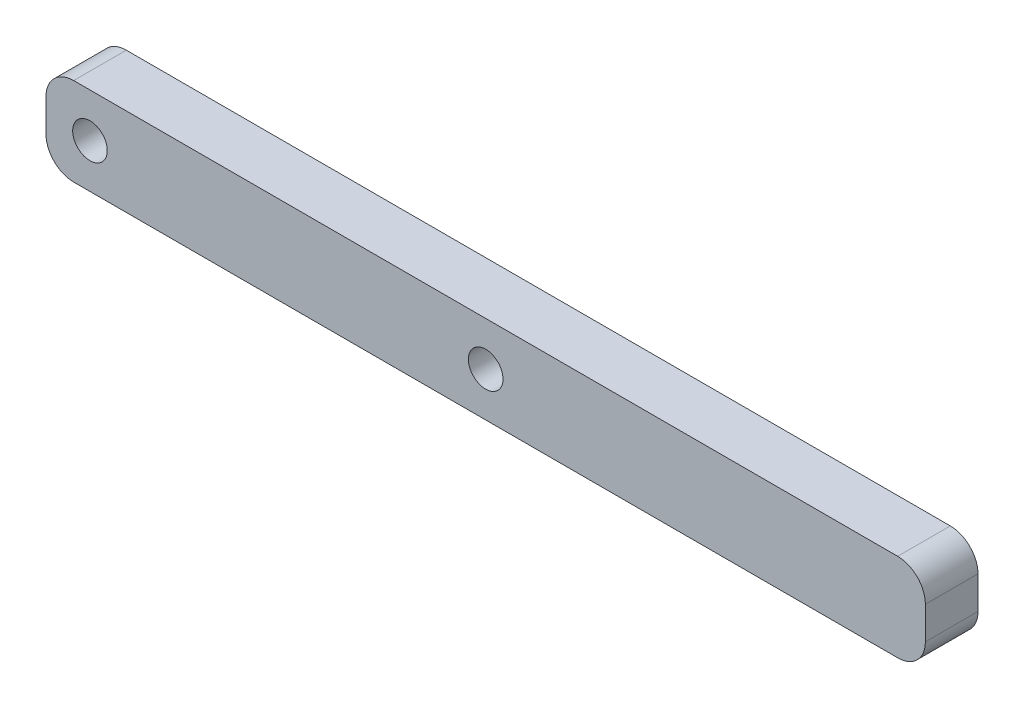
SolidWorks part; units mm, degrees
ref_plane "Front Plane" through (0, 0, 0) normal (0, 0, 1) x (1, 0, 0)
ref_plane "Top Plane" through (0, 0, 0) normal (0, 1, 0) x (1, 0, 0)
ref_plane "Right Plane" through (0, 0, 0) normal (1, 0, 0) x (0, 0, -1)
sketch "Sketch2" plane through (0, 0, 0) normal (0, 0, 1) x (1, 0, 0)
  line L1 (-127, 12.7) -> (0, 12.7)
  line L2 (-127, 12.7) -> (-127, 0)
  line L3 (-127, 0) -> (0, 0)
  line L4 (0, 12.7) -> (0, 0)
  circle A0 centre (-120.65, 6.35) radius 2.5
  circle A1 centre (-63.5, 6.35) radius 2.5
  dimension "D3" = 5
  dimension "D5" = 63.5
  dimension "D6" = 6.35
  dimension "D7" = 6.35
  dimension "D1" = 127
  dimension "D2" = 12.7
  dimension "D4" = 6.35
extrude "Boss-Extrude1" add sketch "Sketch2" along normal blind 7.6
fillet "Fillet1" radius 4 4 edges at (-127, 0, 3.8) (0, 0, 3.8) (0, 12.7, 3.8) (-127, 12.7, 3.8)
